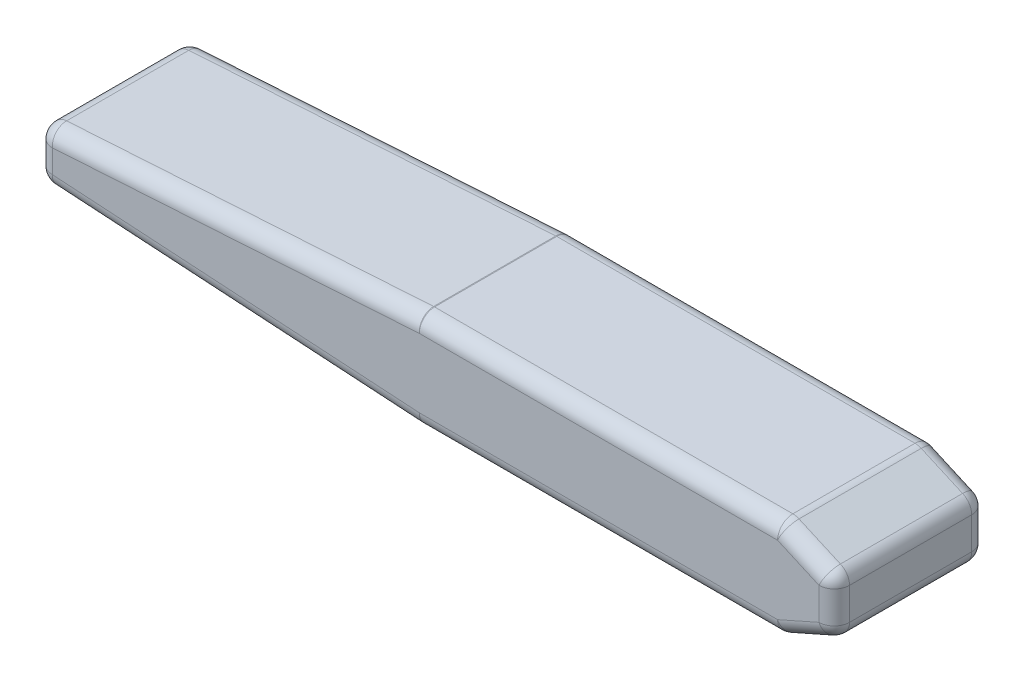
SolidWorks part; units mm, degrees
ref_plane "Спереди" through (0, 0, 0) normal (0, 0, 1) x (1, 0, 0)
ref_plane "Сверху" through (0, 0, 0) normal (0, 1, 0) x (1, 0, 0)
ref_plane "Справа" through (0, 0, 0) normal (1, 0, 0) x (0, 0, -1)
sketch "Sketch1" plane through (0, 0, 0) normal (0, 0, 1) x (1, 0, 0)
  line L0 (0, 1.0492) -> (0, -1.0492)
  line L1 (-0.5951, -1.9635) -> (-3.3066, -3.1643)
  line L2 (-3.7115, -3.25) -> (-27.169, -3.25)
  line L3 (-27.2309, -3.2481) -> (-51.2619, -1.7582)
  line L4 (-52.2, -0.7601) -> (-52.2, 0.7601)
  line L5 (-51.2619, 1.7582) -> (-27.2309, 3.2481)
  line L6 (-27.169, 3.25) -> (-3.7115, 3.25)
  line L7 (-3.3066, 3.1643) -> (-0.5951, 1.9635)
  line L8 (0, 0) -> (-52.2, 0) construction
  arc A0 (-27.169, -3.25) -> (-27.2309, -3.2481) centre (-27.169, -2.25) cw
  arc A1 (-27.2309, 3.2481) -> (-27.169, 3.25) centre (-27.169, 2.25) cw
  arc A2 (-3.7115, 3.25) -> (-3.3066, 3.1643) centre (-3.7115, 2.25) cw
  arc A3 (-0.5951, 1.9635) -> (0, 1.0492) centre (-1, 1.0492) cw
  arc A4 (-0.5951, -1.9635) -> (0, -1.0492) centre (-1, -1.0492) ccw
  arc A5 (-3.3066, -3.1643) -> (-3.7115, -3.25) centre (-3.7115, -2.25) cw
  arc A6 (-52.2, -0.7601) -> (-51.2619, -1.7582) centre (-51.2, -0.7601) ccw
  arc A7 (-52.2, 0.7601) -> (-51.2619, 1.7582) centre (-51.2, 0.7601) cw
  point P13 (-27.2, -3.25)
  point P16 (-27.2, 3.25)
  point P19 (-3.5, 3.25)
  point P22 (0, 1.7)
  point P25 (0, -1.7)
  point P28 (-3.5, -3.25)
  point P31 (-52.2, -1.7)
  point P34 (-52.2, 1.7)
  dimension "D10" = 1
  dimension "D1" = 52.2
  dimension "D2" = 6.5
  dimension "D3" = 3.4
  dimension "D4" = 3.4
  dimension "D5" = 3.5
  dimension "D6" = 3.5
  dimension "D7" = 3.25
  dimension "D8" = 25
  dimension "D9" = 25
extrude "Boss-Extrude1" add sketch "Sketch1" along normal blind 10
fillet "Fillet1" radius 1 32 edges at (-15.4403, -3.25, 0) (-3.5046, -3.2284, 0) (-1.9508, -2.5639, 0) (-0.1619, -1.5947, 0) (0, 0, 0) (-0.1619, 1.5947, 0) (-1.9508, 2.5639, 0) (-3.5046, 3.2284, 0) (-15.4403, 3.25, 0) (-27.2, 3.2495, 0) (-39.2464, 2.5031, 0) (-51.9287, 1.445, 0) (-52.2, 0, 0) (-51.9287, -1.445, 0) (-39.2464, -2.5031, 0) (-27.2, -3.2495, 0) (-39.2464, -2.5031, 10) (-51.9287, -1.445, 10) (-52.2, 0, 10) (-51.9287, 1.445, 10) (-39.2464, 2.5031, 10) (-27.2, 3.2495, 10) (-15.4403, 3.25, 10) (-3.5046, 3.2284, 10) (-1.9508, 2.5639, 10) (-0.1619, 1.5947, 10) (0, 0, 10) (-0.1619, -1.5947, 10) (-1.9508, -2.5639, 10) (-3.5046, -3.2284, 10) (-15.4403, -3.25, 10) (-27.2, -3.2495, 10)
